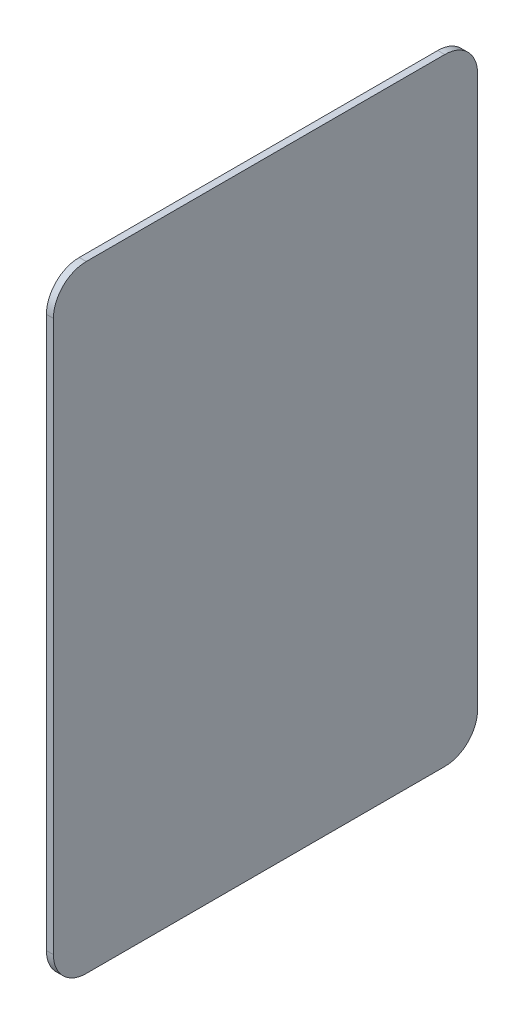
SolidWorks part; units mm, degrees
material "Acrylic (Medium-high impact)"
ref_plane "X-Y Datum" through (0, 0, 0) normal (0, 0, 1) x (1, 0, 0)
ref_plane "X-Z Datum" through (0, 0, 0) normal (0, 1, 0) x (1, 0, 0)
ref_plane "Y-Z Datum" through (0, 0, 0) normal (1, 0, 0) x (0, 0, -1)
sketch "Sketch1" plane through (0, 0, 0) normal (1, 0, 0) x (0, 0, -1)
  line L8 (-81.9489, 94.5314) -> (-81.9489, 219.6264)
  line L9 (-170.8089, 87.0784) -> (-89.4019, 87.0784)
  line L10 (-178.2619, 219.6264) -> (-178.2619, 94.5314)
  line L11 (-89.4019, 227.0794) -> (-170.8089, 227.0794)
  line L12 (-81.9489, 94.5314) -> (-81.9489, 219.6264)
  line L13 (-170.8089, 87.0784) -> (-89.4019, 87.0784)
  line L14 (-178.2619, 219.6264) -> (-178.2619, 94.5314)
  line L15 (-89.4019, 227.0794) -> (-170.8089, 227.0794)
  arc A8 (-89.4019, 87.0784) -> (-81.9489, 94.5314) centre (-89.4019, 94.5314) ccw
  arc A9 (-178.2619, 94.5314) -> (-170.8089, 87.0784) centre (-170.8089, 94.5314) ccw
  arc A10 (-170.8089, 227.0794) -> (-178.2619, 219.6264) centre (-170.8089, 219.6264) ccw
  arc A11 (-81.9489, 219.6264) -> (-89.4019, 227.0794) centre (-89.4019, 219.6264) ccw
  arc A12 (-89.4019, 87.0784) -> (-81.9489, 94.5314) centre (-89.4019, 94.5314) ccw
  arc A13 (-178.2619, 94.5314) -> (-170.8089, 87.0784) centre (-170.8089, 94.5314) ccw
  arc A14 (-170.8089, 227.0794) -> (-178.2619, 219.6264) centre (-170.8089, 219.6264) ccw
  arc A15 (-81.9489, 219.6264) -> (-89.4019, 227.0794) centre (-89.4019, 219.6264) ccw
  dimension "D1" = 0.381
extrude "Boss-Extrude1" add sketch "Sketch1" against normal blind 1.5875
